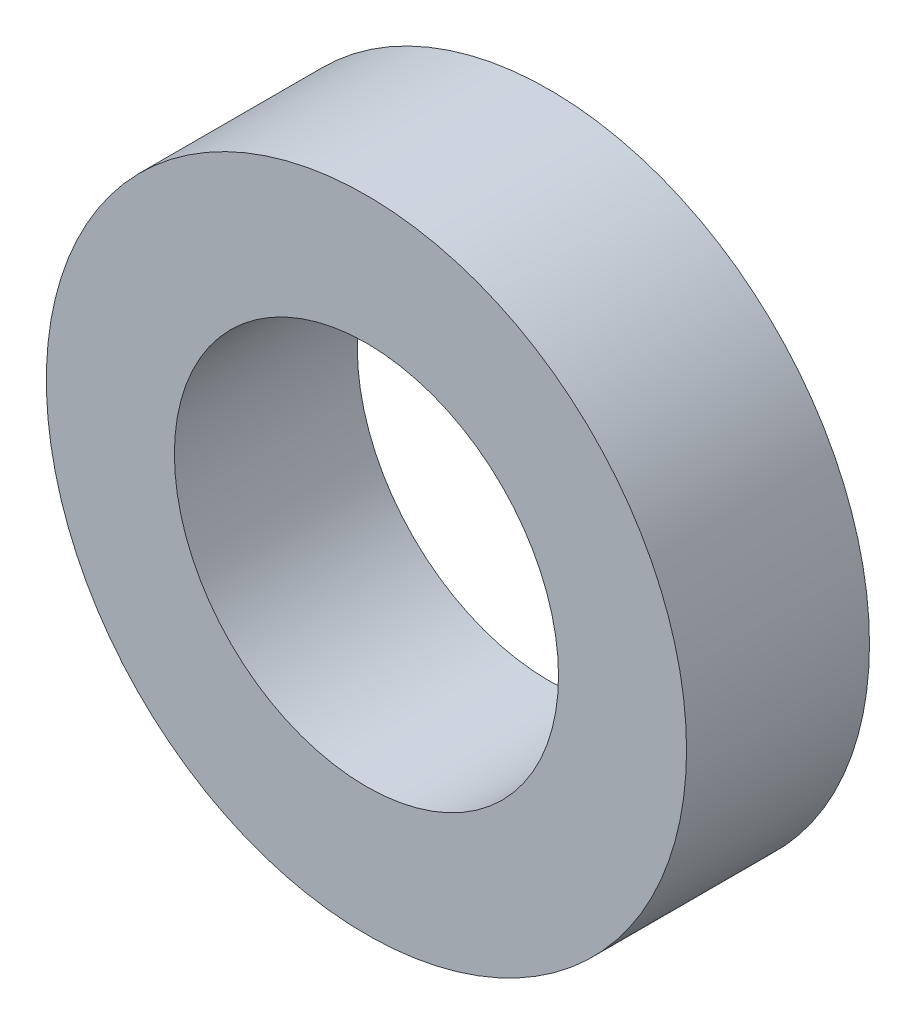
SolidWorks part; units mm, degrees
material "Nylon 6/10"
ref_plane "Face" through (0, 0, 0) normal (0, 0, 1) x (1, 0, 0)
ref_plane "Dessus" through (0, 0, 0) normal (0, 1, 0) x (1, 0, 0)
ref_plane "Droite" through (0, 0, 0) normal (1, 0, 0) x (0, 0, -1)
sketch "Esquisse1" plane through (0, 0, 0) normal (0, 0, 1) x (1, 0, 0)
  circle A0 centre (0, 0) radius 2.1
  circle A1 centre (0, 0) radius 3.5
  dimension "D1" = 4.2
  dimension "D2" = 7
extrude "Boss.-Extru.1" add sketch "Esquisse1" along normal blind 2
